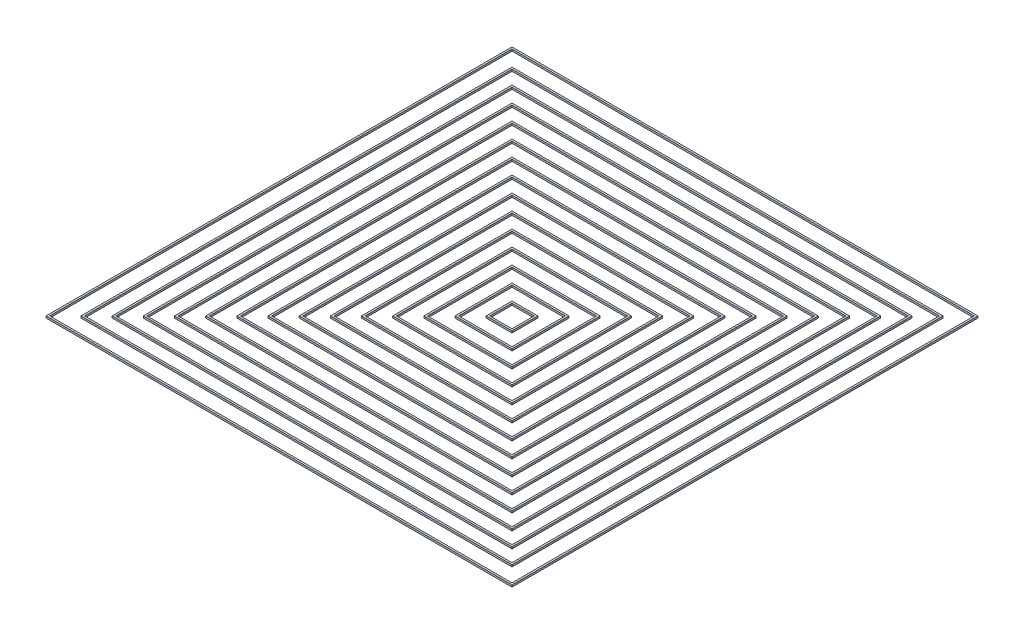
SolidWorks part; units mm, degrees
ref_plane "Front" through (0, 0, 0) normal (0, 0, 1) x (1, 0, 0)
ref_plane "Top" through (0, 0, 0) normal (0, 1, 0) x (1, 0, 0)
ref_plane "Right" through (0, 0, 0) normal (1, 0, 0) x (0, 0, -1)
sketch "Sketch1" plane through (0, 0, 0) normal (0, 1, 0) x (1, 0, 0)
  line L0 (1.2, -1.2) -> (1.2, -297.8)
  line L1 (0, 0) -> (299, 0)
  line L2 (0, 0) -> (0, -299)
  line L3 (0, -299) -> (299, -299)
  line L4 (299, 0) -> (299, -299)
  line L5 (1.2, -297.8) -> (297.8, -297.8)
  line L6 (297.8, -1.2) -> (297.8, -297.8)
  line L7 (1.2, -1.2) -> (297.8, -1.2)
  line L8 (11.2, -287.8) -> (287.8, -287.8)
  line L9 (287.8, -11.2) -> (287.8, -287.8)
  line L10 (11.2, -11.2) -> (287.8, -11.2)
  line L11 (11.2, -11.2) -> (11.2, -287.8)
  line L12 (12.4, -286.6) -> (286.6, -286.6)
  line L13 (286.6, -12.4) -> (286.6, -286.6)
  line L14 (12.4, -12.4) -> (286.6, -12.4)
  line L15 (12.4, -12.4) -> (12.4, -286.6)
  line L16 (22.4, -276.6) -> (276.6, -276.6)
  line L17 (276.6, -22.4) -> (276.6, -276.6)
  line L18 (22.4, -22.4) -> (276.6, -22.4)
  line L19 (22.4, -22.4) -> (22.4, -276.6)
  line L20 (21.2, -277.8) -> (277.8, -277.8)
  line L21 (277.8, -21.2) -> (277.8, -277.8)
  line L22 (21.2, -21.2) -> (277.8, -21.2)
  line L23 (21.2, -21.2) -> (21.2, -277.8)
  line L24 (32.4, -266.6) -> (266.6, -266.6)
  line L25 (266.6, -32.4) -> (266.6, -266.6)
  line L26 (32.4, -32.4) -> (266.6, -32.4)
  line L27 (32.4, -32.4) -> (32.4, -266.6)
  line L28 (31.2, -267.8) -> (267.8, -267.8)
  line L29 (267.8, -31.2) -> (267.8, -267.8)
  line L30 (31.2, -31.2) -> (267.8, -31.2)
  line L31 (31.2, -31.2) -> (31.2, -267.8)
  line L32 (42.4, -256.6) -> (256.6, -256.6)
  line L33 (256.6, -42.4) -> (256.6, -256.6)
  line L34 (42.4, -42.4) -> (256.6, -42.4)
  line L35 (42.4, -42.4) -> (42.4, -256.6)
  line L36 (41.2, -257.8) -> (257.8, -257.8)
  line L37 (257.8, -41.2) -> (257.8, -257.8)
  line L38 (41.2, -41.2) -> (257.8, -41.2)
  line L39 (41.2, -41.2) -> (41.2, -257.8)
  line L40 (51.2, -247.8) -> (247.8, -247.8)
  line L41 (247.8, -51.2) -> (247.8, -247.8)
  line L42 (51.2, -51.2) -> (247.8, -51.2)
  line L43 (51.2, -51.2) -> (51.2, -247.8)
  line L44 (52.4, -246.6) -> (246.6, -246.6)
  line L45 (246.6, -52.4) -> (246.6, -246.6)
  line L46 (52.4, -52.4) -> (246.6, -52.4)
  line L47 (52.4, -52.4) -> (52.4, -246.6)
  line L48 (62.4, -236.6) -> (236.6, -236.6)
  line L49 (236.6, -62.4) -> (236.6, -236.6)
  line L50 (62.4, -62.4) -> (236.6, -62.4)
  line L51 (62.4, -62.4) -> (62.4, -236.6)
  line L52 (61.2, -237.8) -> (237.8, -237.8)
  line L53 (237.8, -61.2) -> (237.8, -237.8)
  line L54 (61.2, -61.2) -> (237.8, -61.2)
  line L55 (61.2, -61.2) -> (61.2, -237.8)
  line L56 (72.4, -226.6) -> (226.6, -226.6)
  line L57 (226.6, -72.4) -> (226.6, -226.6)
  line L58 (72.4, -72.4) -> (226.6, -72.4)
  line L59 (72.4, -72.4) -> (72.4, -226.6)
  line L60 (71.2, -227.8) -> (227.8, -227.8)
  line L61 (227.8, -71.2) -> (227.8, -227.8)
  line L62 (71.2, -71.2) -> (227.8, -71.2)
  line L63 (71.2, -71.2) -> (71.2, -227.8)
  line L64 (101.2, -197.8) -> (197.8, -197.8)
  line L65 (197.8, -101.2) -> (197.8, -197.8)
  line L66 (101.2, -101.2) -> (197.8, -101.2)
  line L67 (101.2, -101.2) -> (101.2, -197.8)
  line L68 (102.4, -196.6) -> (196.6, -196.6)
  line L69 (196.6, -102.4) -> (196.6, -196.6)
  line L70 (102.4, -102.4) -> (196.6, -102.4)
  line L71 (102.4, -102.4) -> (102.4, -196.6)
  line L72 (92.4, -206.6) -> (206.6, -206.6)
  line L73 (206.6, -92.4) -> (206.6, -206.6)
  line L74 (92.4, -92.4) -> (206.6, -92.4)
  line L75 (92.4, -92.4) -> (92.4, -206.6)
  line L76 (91.2, -207.8) -> (207.8, -207.8)
  line L77 (207.8, -91.2) -> (207.8, -207.8)
  line L78 (91.2, -91.2) -> (207.8, -91.2)
  line L79 (91.2, -91.2) -> (91.2, -207.8)
  line L80 (82.4, -216.6) -> (216.6, -216.6)
  line L81 (216.6, -82.4) -> (216.6, -216.6)
  line L82 (82.4, -82.4) -> (216.6, -82.4)
  line L83 (82.4, -82.4) -> (82.4, -216.6)
  line L84 (81.2, -217.8) -> (217.8, -217.8)
  line L85 (217.8, -81.2) -> (217.8, -217.8)
  line L86 (81.2, -81.2) -> (217.8, -81.2)
  line L87 (81.2, -81.2) -> (81.2, -217.8)
  line L88 (122.4, -176.6) -> (176.6, -176.6)
  line L89 (176.6, -122.4) -> (176.6, -176.6)
  line L90 (122.4, -122.4) -> (176.6, -122.4)
  line L91 (122.4, -122.4) -> (122.4, -176.6)
  line L92 (121.2, -177.8) -> (177.8, -177.8)
  line L93 (177.8, -121.2) -> (177.8, -177.8)
  line L94 (121.2, -121.2) -> (177.8, -121.2)
  line L95 (121.2, -121.2) -> (121.2, -177.8)
  line L96 (112.4, -186.6) -> (186.6, -186.6)
  line L97 (186.6, -112.4) -> (186.6, -186.6)
  line L98 (112.4, -112.4) -> (186.6, -112.4)
  line L99 (112.4, -112.4) -> (112.4, -186.6)
  line L100 (111.2, -187.8) -> (187.8, -187.8)
  line L101 (187.8, -111.2) -> (187.8, -187.8)
  line L102 (111.2, -111.2) -> (187.8, -111.2)
  line L103 (111.2, -111.2) -> (111.2, -187.8)
  line L104 (156.6, -142.4) -> (156.6, -156.6)
  line L105 (142.4, -156.6) -> (156.6, -156.6)
  line L106 (142.4, -142.4) -> (142.4, -156.6)
  line L107 (142.4, -142.4) -> (156.6, -142.4)
  line L108 (157.8, -141.2) -> (157.8, -157.8)
  line L109 (141.2, -157.8) -> (157.8, -157.8)
  line L110 (141.2, -141.2) -> (141.2, -157.8)
  line L111 (141.2, -141.2) -> (157.8, -141.2)
  line L112 (166.6, -132.4) -> (166.6, -166.6)
  line L113 (132.4, -166.6) -> (166.6, -166.6)
  line L114 (132.4, -132.4) -> (132.4, -166.6)
  line L115 (132.4, -132.4) -> (166.6, -132.4)
  line L116 (167.8, -131.2) -> (167.8, -167.8)
  line L117 (131.2, -167.8) -> (167.8, -167.8)
  line L118 (131.2, -131.2) -> (131.2, -167.8)
  line L119 (131.2, -131.2) -> (167.8, -131.2)
  dimension "D1" = 299
  dimension "D2" = 299
  dimension "D3" = 1.2
  dimension "D4" = 10
  dimension "D5" = 1.2
  dimension "D6" = 10
  dimension "D7" = 10
  dimension "D8" = 10
  dimension "D9" = 10
  dimension "D10" = 10
  dimension "D11" = 10
  dimension "D12" = 30
  dimension "D13" = 20
  dimension "D14" = 20
extrude "Boss-Extrude2" add sketch "Sketch1" along normal blind 1.2 contours L4 L1 L2 L3 L0 L7 L6 L5 | L10 L11 L8 L9 L15 L14 L13 L12 | L22 L23 L20 L21 L19 L18 L17 L16 | L30 L31 L28 L29 L27 L26 L25 L24 | L38 L39 L36 L37 L35 L34 L33 L32 | L42 L43 L40 L41 L47 L46 L45 L44 | L54 L55 L52 L53 L51 L50 L49 L48 | L62 L63 L60 L61 L59 L58 L57 L56 | L86 L87 L84 L85 L83 L82 L81 L80 | L78 L79 L76 L77 L75 L74 L73 L72 | L66 L67 L64 L65 L71 L70 L69 L68 | L102 L103 L100 L101 L99 L98 L97 L96 | L94 L95 L92 L93 L91 L90 L89 L88 | L119 L118 L117 L116 L114 L115 L112 L113 | L111 L110 L109 L108 L106 L107 L104 L105
